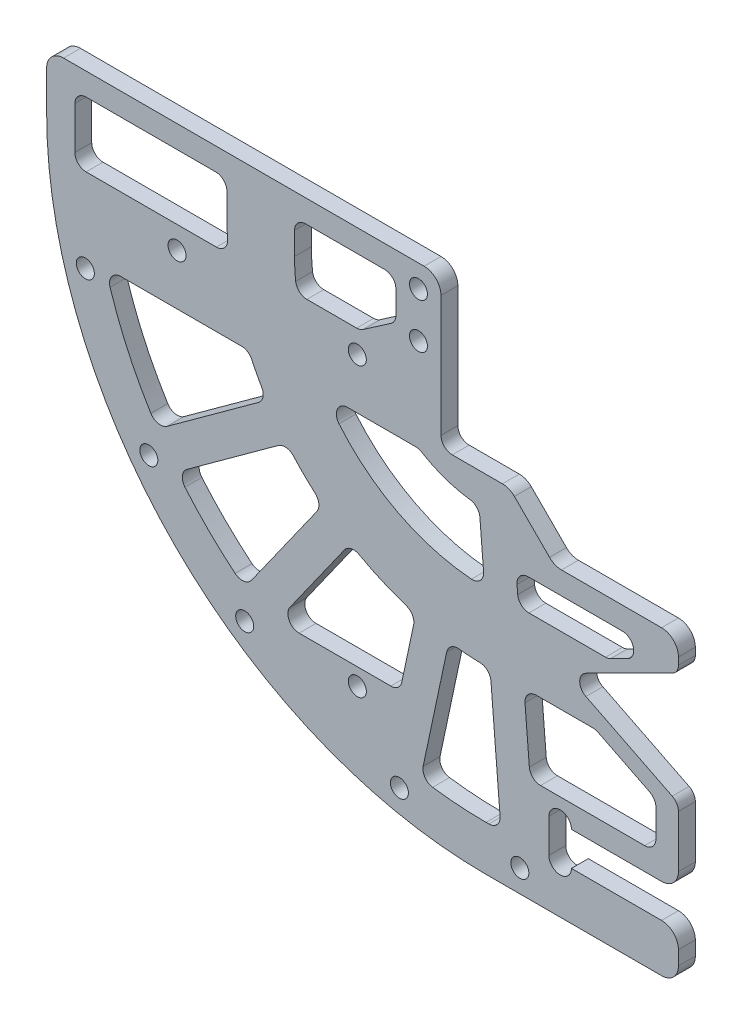
SolidWorks part; units mm, degrees
material "A-玻璃纤维"
ref_plane "前视基准面" through (0, 0, 0) normal (0, 0, 1) x (1, 0, 0)
ref_plane "上视基准面" through (0, 0, 0) normal (0, 1, 0) x (1, 0, 0)
ref_plane "右视基准面" through (0, 0, 0) normal (1, 0, 0) x (0, 0, -1)
sketch "草图1" plane through (0, 0, 0) normal (0, 0, 1) x (1, 0, 0)
  line L0 (-139.1546, 76.5) -> (-139.1546, -33.6254) construction
  line L1 (-91.6495, 50) -> (0, 50) construction
  line L2 (-90.2793, 53) -> (-5.3283, 53) construction
  line L4 (-99.1546, 26.5) -> (0, 26.5) construction
  line L6 (-99.1546, 26.5) -> (-88, 26.5) construction
  line L7 (0, 26.5) -> (0, 0) construction
  line L8 (-88, 26.5) -> (-88, -20.8435) construction
  arc A0 (-139.1546, 66.5) -> (-99.1546, 26.5) centre (-99.1546, 66.5) ccw
  dimension "D1" = 3
  dimension "D4" = 80
  dimension "D3" = 23.5
  dimension "D7" = 10
  dimension "D8" = 88
  dimension "D9" = 11.1546
sketch "草图2" plane through (0, 0, 0) normal (0, 0, 1) x (1, 0, 0)
  line L0 (0, 0) -> (-88, 0) construction
  line L1 (-88, 26.5) -> (-88, -20.8435) construction
  line L2 (0, 3) -> (-88, 3) construction
  line L3 (-99.1546, 26.5) -> (0, 26.5) construction
  line L4 (-139.1546, 76.5) -> (-139.1546, -33.6254) construction
  line L5 (-99.1546, 26.5) -> (-88, 26.5) construction
  line L6 (-139.1546, 76.5) -> (-139.1546, 66.5) construction
  line L7 (-88, 3) -> (-88, 26.5) construction
  line L8 (-161.1546, 76.5) -> (-161.1546, 66.5) construction
  line L9 (-99.1546, 4.5) -> (-88, 4.5) construction
  line L10 (-117.1546, 76.5) -> (-117.1546, 66.5) construction
  line L11 (-99.1546, 48.5) -> (-88, 48.5) construction
  line L12 (-63.5, 3) -> (-63.5, 50) construction
  line L13 (-162.1546, 76.5) -> (-162.1546, 66.5) construction
  line L14 (-99.1546, 3.5) -> (-88, 3.5) construction
  line L15 (-164.6546, 76.5) -> (-164.6546, 66.5) construction
  line L16 (-99.1546, 1) -> (-88, 1) construction
  line L17 (-169.1546, 76.5) -> (-169.1546, 66.5) construction
  line L18 (-99.1546, -3.5) -> (-88, -3.5) construction
  line L19 (-177.1546, 76.5) -> (-177.1546, 66.5)
  line L20 (-99.1546, -11.5) -> (-88, -11.5)
  line L21 (-177.1546, 76.5) -> (-162.1546, 76.5) construction
  line L22 (-88, 3.5) -> (-88, -11.5) construction
  line L23 (-99.1546, 66.5) -> (-99.1546, 1) construction
  line L24 (-99.1546, 66.5) -> (-106.9101, 1.4608) construction
  line L25 (-164.6546, 75.2931) -> (-164.6546, 78.7931) construction
  line L26 (-91.6495, 50) -> (0, 50) construction
  line L27 (0, -3) -> (-88, -3) construction
  line L33 (-65, 3) -> (-88, 3)
  line L34 (-88, 3) -> (-88, -3)
  line L35 (-88, -3) -> (-65, -3)
  line L36 (-65, -3) -> (-65, -11.5)
  line L37 (-65, -11.5) -> (-88, -11.5)
  line L38 (-177.1546, 76.5) -> (-107.1546, 76.5)
  line L39 (-107.1546, 76.5) -> (-107.1546, 50)
  line L40 (-107.1546, 50) -> (-65, 50)
  line L41 (-65, 50) -> (-65, 35.9434)
  line L42 (-65, 35.9434) -> (-62.5, 34.5)
  line L43 (-62.5, 34.5) -> (-62.5, 18.5)
  line L44 (-62.5, 18.5) -> (-65, 17.0566)
  line L45 (-65, 17.0566) -> (-65, 3)
  line L46 (-62.5, 26.5) -> (-47.2977, 26.5) construction
  arc A0 (-139.1546, 66.5) -> (-99.1546, 26.5) centre (-99.1546, 66.5) ccw construction
  arc A1 (-139.1546, 66.5) -> (-99.1546, 26.5) centre (-99.1546, 66.5) ccw construction
  arc A2 (-161.1546, 66.5) -> (-99.1546, 4.5) centre (-99.1546, 66.5) ccw construction
  arc A3 (-117.1546, 66.5) -> (-99.1546, 48.5) centre (-99.1546, 66.5) ccw construction
  arc A4 (-162.1546, 66.5) -> (-99.1546, 3.5) centre (-99.1546, 66.5) ccw construction
  arc A5 (-164.6546, 66.5) -> (-99.1546, 1) centre (-99.1546, 66.5) ccw construction
  arc A6 (-169.1546, 66.5) -> (-99.1546, -3.5) centre (-99.1546, 66.5) ccw construction
  arc A7 (-177.1546, 66.5) -> (-99.1546, -11.5) centre (-99.1546, 66.5) ccw
  circle A8 centre (-91.7546, 1) radius 3.5 construction
  circle A9 centre (-99.1546, 1) radius 3.5 construction
  circle A10 centre (-106.9101, 1.4608) radius 3.5 construction
  circle A11 centre (-114.5564, 2.8366) radius 3.5 construction
  circle A12 centre (-121.9861, 5.108) radius 3.5 construction
  circle A13 centre (-129.0945, 8.2432) radius 3.5 construction
  circle A14 centre (-135.7817, 12.198) radius 3.5 construction
  circle A15 centre (-141.9536, 16.9168) radius 3.5 construction
  circle A16 centre (-147.5234, 22.3332) radius 3.5 construction
  circle A17 centre (-152.4127, 28.3709) radius 3.5 construction
  circle A18 centre (-156.5527, 34.9451) radius 3.5 construction
  circle A19 centre (-159.8851, 41.9633) radius 3.5 construction
  circle A20 centre (-162.3632, 49.3266) radius 3.5 construction
  circle A21 centre (-163.9519, 56.9316) radius 3.5 construction
  circle A22 centre (-164.6291, 64.6711) radius 3.5 construction
  circle A23 centre (-164.6546, 72.3711) radius 3.5 construction
  arc A24 (-139.1546, 66.5) -> (-99.1546, 26.5) centre (-99.1546, 66.5) ccw construction
  dimension "D8" = 7
  dimension "D9" = 7
  dimension "D10" = 7.4
  dimension "D13" = 7
  dimension "D16" = 24.5
  dimension "D1" = 3
  dimension "D2" = 22
  dimension "D4" = 1
  dimension "D12" = 6.8
  dimension "D14" = 7.7691
  dimension "D15" = 7.7
  dimension "D17" = 3
  dimension "D18" = 120
  dimension "D19" = 120
  dimension "D20" = 23
  dimension "D21" = 1
  dimension "D22" = 16
  dimension "D23" = 10
  dimension "D3" = 22
  dimension "D5" = 3.5
  dimension "D6" = 7
  dimension "D7" = 8
  dimension "D11" = 14
extrude "凸台-拉伸1" add sketch "草图2" along normal blind 3 contours L39 L40 L41 L42 L43 L44 L45 L33 L34 L35 L36 L37 L20 A7 L19 L38
sketch "草图3" plane through (0, 0, 3) normal (0, 0, 1) x (1, 0, 0)
  line L0 (-88, 3) -> (-183.1097, 3) construction
  line L1 (-137, 6) -> (-122, 6) construction
  line L2 (-117, 9) -> (-157, 9) construction
  line L3 (-117, 9) -> (-117, 3) construction
  line L4 (-117, 3) -> (-157, 3) construction
  line L5 (-157, 9) -> (-157, 3) construction
  line L6 (-117, 9) -> (-157, 3) construction
  line L7 (-117, 3) -> (-157, 9) construction
  line L8 (-137, 6) -> (-142, 6) construction
  circle A0 centre (-142, 6) radius 1.6
  circle A1 centre (-122, 6) radius 1.6
  point P3 (-137, 6)
  dimension "D5" = 5
  dimension "D6" = 3.2
  dimension "D7" = 3.2
  dimension "D1" = 6
  dimension "D2" = 40
  dimension "D3" = 157
  dimension "D4" = 15
extrude "切除-拉伸1" cut sketch "草图3" against normal blind 10
sketch "草图4" plane through (0, 0, 3) normal (0, 0, 1) x (1, 0, 0)
  line L0 (-65, -11.5) -> (-99.1546, -11.5) construction
  line L1 (-65, -11.5) -> (-99.1546, -11.5) construction
  line L2 (-65, -7.5) -> (-99.1546, -7.5) construction
  line L3 (-185.4367, 66.5) -> (-99.1546, 66.5) construction
  line L4 (-99.1546, 66.5) -> (-170.288, 46.1028) construction
  line L5 (-159.0218, 23.0039) -> (-99.1546, 66.5) construction
  line L6 (-99.1546, 66.5) -> (-114.5401, -5.8829) construction
  line L7 (-99.1546, 66.5) -> (-99.1546, -11.5) construction
  arc A0 (-177.1546, 66.5) -> (-99.1546, -11.5) centre (-99.1546, 66.5) ccw construction
  arc A1 (-177.1546, 66.5) -> (-99.1546, -11.5) centre (-99.1546, 66.5) ccw construction
  arc A2 (-173.1546, 66.5) -> (-99.1546, -7.5) centre (-99.1546, 66.5) ccw construction
  circle A3 centre (-170.288, 46.1028) radius 1.6
  circle A4 centre (-159.0218, 23.0039) radius 1.6
  circle A5 centre (-114.5401, -5.8829) radius 1.6
  circle A6 centre (-93.1546, -7.5) radius 1.6
  dimension "D2" = 3.2
  dimension "D3" = 3.2
  dimension "D4" = 3.2
  dimension "D5" = 3.2
  dimension "D6" = 6
  dimension "D7" = 12
  dimension "D8" = 20
  dimension "D9" = 16
  dimension "D1" = 4
extrude "切除-拉伸2" cut sketch "草图4" against normal blind 10
sketch "草图5" plane through (0, 0, 3) normal (0, 0, 1) x (1, 0, 0)
  line L0 (-65, 3) -> (-88, 3) construction
  line L1 (-88, -3) -> (-65, -3) construction
  line L2 (-88, 3) -> (-88, -3) construction
  circle A0 centre (-86, 3) radius 2
  circle A1 centre (-86, -3) radius 2
  dimension "D1" = 4
  dimension "D2" = 4
extrude "切除-拉伸3" cut sketch "草图5" against normal blind 10
sketch "草图6" plane through (0, 0, 3) normal (0, 0, 1) x (1, 0, 0)
  line L0 (-111.1546, 64.5) -> (-111.1546, 72.5) construction
  line L1 (-177.1546, 76.5) -> (-107.1546, 76.5) construction
  line L3 (-99.1546, 53) -> (-99.1546, 69.0606) construction
  circle A0 centre (-111.1546, 72.5) radius 1.6
  circle A1 centre (-111.1546, 64.5) radius 1.6
  dimension "D1" = 3.2
  dimension "D2" = 3.2
  dimension "D4" = 4
  dimension "D5" = 12
  dimension "D3" = 8
extrude "切除-拉伸4" cut sketch "草图6" against normal blind 3
sketch "草图7" plane through (0, 0, 3) normal (0, 0, 1) x (1, 0, 0)
  line L0 (-107.1546, 50) -> (-161.0256, 50) construction
  line L1 (-154.0101, 57) -> (-122.0101, 57) construction
  line L2 (-138.0101, 57) -> (-138.0101, 61.0464) construction
  line L4 (-162.0101, 61) -> (-114.0101, 61) construction
  line L5 (-162.0101, 61) -> (-162.0101, 53) construction
  line L6 (-162.0101, 53) -> (-114.0101, 53) construction
  line L7 (-114.0101, 61) -> (-114.0101, 53) construction
  line L8 (-162.0101, 61) -> (-114.0101, 53) construction
  line L9 (-162.0101, 53) -> (-114.0101, 61) construction
  arc A0 (-139.1546, 66.5) -> (-99.1546, 26.5) centre (-99.1546, 66.5) ccw construction
  arc A1 (-139.1546, 66.5) -> (-99.1546, 26.5) centre (-99.1546, 66.5) ccw construction
  circle A4 centre (-111.1546, 64.5) radius 1.6 construction
  circle A5 centre (-154.0101, 57) radius 1.6
  circle A6 centre (-122.0101, 57) radius 1.6
  dimension "D1" = 7
  dimension "D6" = 3.2
  dimension "D7" = 3.2
  dimension "D2" = 32
  dimension "D3" = 8
  dimension "D4" = 48
  dimension "D5" = 3.5
extrude "切除-拉伸5" cut sketch "草图7" against normal blind 3
fillet "圆角1" radius 2 1 edges at (-107.1546, 50, 1.5)
sketch "草图8" plane through (0, 0, 3) normal (0, 0, 1) x (1, 0, 0)
  line L0 (-95, 50) -> (-87, 42)
  line L1 (-105.1546, 50) -> (-65, 50) construction
  line L2 (-87, 42) -> (-65, 42)
  line L3 (-65, 50) -> (-65, 35.9434) construction
  line L4 (-65, 42) -> (-65, 50)
  line L5 (-65, 50) -> (-95, 50)
  dimension "D1" = 8
  dimension "D2" = 135
  dimension "D3" = 22
extrude "切除-拉伸6" cut sketch "草图8" against normal blind 11.6
fillet "圆角2" radius 3 8 edges at (-65, -11.5, 1.5) (-65, -3, 1.5) (-65, 3, 1.5) (-177.1546, 76.5, 1.5) (-107.1546, 76.5, 1.5) (-95, 50, 1.5) (-87, 42, 1.5) (-65, 42, 1.5)
sketch "草图9" plane through (0, 0, 3) normal (0, 0, 1) x (1, 0, 0)
  line L0 (-99.1546, 26.5) -> (0, 26.5) construction
  line L1 (-139.1546, 76.5) -> (-139.1546, -33.6254) construction
  line L2 (-99.1546, 26.5) -> (0, 26.5) construction
  line L3 (-139.1546, 76.5) -> (-139.1546, 66.5) construction
  line L4 (-145.1546, 72.5) -> (-145.1546, 66.5)
  line L5 (-99.1546, 20.5) -> (-98.4347, 20.5)
  line L6 (-133.1546, 72.5) -> (-133.1546, 66.5)
  line L7 (-101.7131, 60.933) -> (-101.3333, 56.2498)
  line L8 (-172.1546, 61) -> (-144.8246, 61)
  line L9 (-166.6657, 48) -> (-141.2705, 48)
  line L10 (-133.1546, 72.5) -> (-115.1546, 72.5)
  line L11 (-115.1546, 72.5) -> (-115.1546, 65.3828)
  line L12 (-115.1546, 65.3828) -> (-121.4982, 61)
  line L13 (-122.0101, 57) -> (-111.1546, 64.5) construction
  line L14 (-174.1546, 76.5) -> (-110.1546, 76.5) construction
  line L15 (-145.1546, 72.5) -> (-172.1546, 72.5)
  line L16 (-172.1546, 72.5) -> (-172.1546, 61)
  line L17 (-177.1546, 73.5) -> (-177.1546, 66.5) construction
  line L18 (-145.1546, 76.5) -> (-145.1546, 66.5) construction
  line L19 (-133.1546, 76.5) -> (-133.1546, 66.5) construction
  line L20 (-132.7068, 61) -> (-121.4982, 61)
  line L21 (-99.1546, 66.5) -> (-159.0218, 23.0039) construction
  line L22 (-99.1546, 66.5) -> (-142, 6) construction
  line L23 (-101.6028, 68.2338) -> (-112.1362, 53.3601)
  line L24 (-99.1546, 66.5) -> (-114.5401, -5.8829) construction
  line L25 (-99.1546, 66.5) -> (-93.1546, -7.5) construction
  line L26 (-102.089, 67.1237) -> (-105.1135, 52.8949)
  line L27 (-102.1448, 66.2576) -> (-101.3333, 56.2498)
  line L28 (-101.7131, 60.933) -> (-112.1362, 53.3601)
  line L29 (-96.7063, 64.7662) -> (-105.1135, 52.8949)
  line L30 (-96.2201, 65.8763) -> (-98.3077, 56.0551)
  line L31 (-127.6809, 48) -> (-111.0605, 48)
  line L32 (-97.3912, 64.0729) -> (-112.1362, 53.3601)
  line L34 (-101.7131, 60.933) -> (-157.2585, 20.5768) construction
  line L35 (-99.1546, -3.5) -> (-68, -3.5)
  line L36 (-99.1546, -3.5) -> (-96.4888, -3.5)
  line L37 (-97.3912, 64.0729) -> (-157.2585, 20.5768) construction
  line L38 (-101.6028, 68.2338) -> (-144.4482, 7.7338) construction
  line L39 (-96.7063, 64.7662) -> (-139.5518, 4.2662) construction
  line L40 (-102.089, 67.1237) -> (-117.4745, -5.2592) construction
  line L41 (-96.2201, 65.8763) -> (-111.6056, -6.5067) construction
  line L42 (-102.1448, 66.2576) -> (-96.1448, -7.7424) construction
  line L43 (-136.1993, 9) -> (-114.4436, 9)
  line L45 (-138.0535, 41.9465) -> (-157.4971, 27.8199)
  line L46 (-134.5268, 37.0924) -> (-153.9704, 22.9658)
  line L47 (-128.1314, 30.774) -> (-142.0214, 11.1607)
  line L48 (-123.2349, 27.3064) -> (-136.1993, 9)
  line L49 (-111.6326, 22.2247) -> (-114.4436, 9)
  line L50 (-105.7637, 20.9773) -> (-110.7606, -2.5312)
  line L51 (-98.4347, 20.5) -> (-96.4888, -3.5)
  line L52 (-92.415, 20.5) -> (-69, 20.5)
  line L53 (-99.1546, 20.5) -> (0, 20.5) construction
  line L54 (-92.415, 20.5) -> (-91.3204, 7)
  line L55 (-93.388, 32.5) -> (-66.388, 32.5)
  line L56 (-99.1546, 32.5) -> (0, 32.5) construction
  line L57 (-100.3834, 44.5343) -> (-99.4078, 32.5009)
  line L58 (-101.7131, 60.933) -> (-96.1448, -7.7424) construction
  line L59 (-93.388, 32.5) -> (-93.8339, 38)
  line L60 (-93.8339, 38) -> (-69.5634, 38)
  line L61 (-69.5634, 38) -> (-66.388, 32.5)
  line L62 (-85.7574, 42) -> (-68, 42) construction
  line L64 (-91.3204, 7) -> (-69, 7)
  line L65 (-69, 7) -> (-69, 20.5)
  line L66 (-65, 17.0566) -> (-65, 6) construction
  line L67 (-68, 3) -> (-84, 3) construction
  arc A0 (-139.1546, 66.5) -> (-99.1546, 26.5) centre (-99.1546, 66.5) ccw construction
  arc A1 (-139.1546, 66.5) -> (-99.1546, 26.5) centre (-99.1546, 66.5) ccw construction
  arc A2 (-145.1546, 66.5) -> (-144.8246, 61) centre (-99.1546, 66.5) ccw
  arc A3 (-133.1546, 66.5) -> (-132.7068, 61) centre (-99.1546, 66.5) ccw
  circle A4 centre (-122.0101, 57) radius 1.6 construction
  circle A5 centre (-111.1546, 64.5) radius 1.6 construction
  arc A6 (-111.0605, 48) -> (-100.3834, 44.5343) centre (-99.1546, 66.5) ccw
  arc A7 (-133.1546, 66.5) -> (-99.1546, 32.5) centre (-99.1546, 66.5) ccw construction
  arc A8 (-141.2705, 48) -> (-138.0535, 41.9465) centre (-99.1546, 66.5) ccw
  arc A9 (-145.1546, 66.5) -> (-99.1546, 20.5) centre (-99.1546, 66.5) ccw construction
  arc A11 (-166.6657, 48) -> (-157.4971, 27.8199) centre (-99.1546, 66.5) ccw
  arc A12 (-169.1546, 66.5) -> (-99.1546, -3.5) centre (-99.1546, 66.5) ccw
  arc A13 (-153.9704, 22.9658) -> (-142.0214, 11.1607) centre (-99.1546, 66.5) ccw
  arc A14 (-134.5268, 37.0924) -> (-128.1314, 30.774) centre (-99.1546, 66.5) ccw
  arc A15 (-110.7606, -2.5312) -> (-99.1546, -3.5) centre (-99.1546, 66.5) ccw
  circle A16 centre (-122, 6) radius 1.6 construction
  arc A17 (-123.2349, 27.3064) -> (-111.6326, 22.2247) centre (-99.1546, 66.5) ccw
  arc A18 (-105.7637, 20.9773) -> (-99.1546, 20.5) centre (-99.1546, 66.5) ccw
  arc A20 (-127.6809, 48) -> (-99.4078, 32.5009) centre (-99.1546, 66.5) ccw
  dimension "D3" = 4
  dimension "D4" = 9
  dimension "D5" = 4
  dimension "D13" = 70
  dimension "D15" = 68
  dimension "D16" = 44
  dimension "D6" = 3
  dimension "D7" = 4
  dimension "D8" = 5
  dimension "D9" = 3
  dimension "D12" = 3
  dimension "D14" = 3
  dimension "D17" = 3
  dimension "D18" = 27
  dimension "D19" = 60
  dimension "D20" = 4
  dimension "D21" = 6
  dimension "D22" = 4
  dimension "D23" = 4
  dimension "D1" = 6
  dimension "D2" = 6
  dimension "D10" = 3
  dimension "D11" = 8
extrude "切除-拉伸7" cut sketch "草图9" against normal blind 11.6 contours A2 L4 L15 L16 L8 | L6 A3 L20 L12 L11 L10 | L31 A20 L57 A6 | L9 A11 L45 A8 | A17 L48 L43 L49 | A18 L50 A15 L36 L51 L5 | A14 L46 A13 L47 | L61 L60 L59 L55 | L64 L65 L52 L54
sketch "草图11" plane through (0, 0, 3) normal (0, 0, 1) x (1, 0, 0)
  line L0 (-65, 36.5) -> (-85, 26.5)
  line L1 (-65, 39) -> (-65, 35.9434) construction
  line L2 (-99.1546, 26.5) -> (0, 26.5) construction
  line L3 (-85, 26.5) -> (-59.8005, 26.5) construction
  line L4 (-65, 36.5) -> (-59.8005, 36.5)
  line L5 (-59.8005, 36.5) -> (-59.8005, 16.5)
  line L6 (-62.5, 34.5) -> (-62.5, 18.5) construction
  line L7 (-65, 17.0566) -> (-65, 6) construction
  line L8 (-65, 16.5) -> (-59.8005, 16.5)
  line L9 (-65, 16.5) -> (-85, 26.5)
  dimension "D1" = 10
  dimension "D2" = 2.6995
  dimension "D3" = 20
sketch "草图13" plane through (0, 0, 3) normal (0, 0, 1) x (1, 0, 0)
  line L0 (-74.0498, 34.2111) -> (-77.4721, 32.5)
  line L1 (-69.5634, 38) -> (-66.388, 32.5) construction
  line L2 (-93.388, 32.5) -> (-66.388, 32.5) construction
  line L3 (-77.4721, 32.5) -> (-73, 32.5)
  line L4 (-65, 36.5) -> (-85, 26.5) construction
  line L5 (-73, 32.5) -> (-67.8691, 35.0654)
  line L6 (-67.8691, 35.0654) -> (-68.8709, 36.8006)
  line L7 (-93.8339, 38) -> (-69.5634, 38) construction
  line L8 (-74.9443, 38) -> (-69.5634, 38)
  line L9 (-69.5634, 38) -> (-68.8709, 36.8006)
  line L10 (-79.7082, 20.5) -> (-73, 20.5)
  line L11 (-92.415, 20.5) -> (-69, 20.5) construction
  line L12 (-65, 16.5) -> (-85, 26.5) construction
  line L13 (-73, 20.5) -> (-69, 18.5)
  line L14 (-69, 18.5) -> (-69, 15.1459)
  line L15 (-69, 7) -> (-69, 20.5) construction
  line L16 (-69, 15.1459) -> (-79.7082, 20.5)
  arc A0 (-74.0498, 34.2111) -> (-74.9443, 38) centre (-74.9443, 36) ccw
  dimension "D2" = 4
  dimension "D1" = 2
  dimension "D3" = 3
extrude "凸台-拉伸2" add sketch "草图13" against normal up to surface (3 mm away) up to face at (-151.1009, 41.3353, 0)
extrude "切除-拉伸8" cut sketch "草图11" against normal through all contours L4 L5 L8 L9 L0
fillet "圆角3" radius 2 37 edges at (-111.6326, 22.2247, 1.5) (-114.4436, 9, 1.5) (-136.1993, 9, 1.5) (-123.2349, 27.3064, 1.5) (-111.0605, 48, 1.5) (-100.3834, 44.5343, 1.5) (-99.4078, 32.5009, 1.5) (-127.6809, 48, 1.5) (-115.1546, 72.5, 1.5) (-115.1546, 65.3828, 1.5) (-121.4982, 61, 1.5) (-132.7068, 61, 1.5) (-133.1546, 72.5, 1.5) (-128.1314, 30.774, 1.5) (-142.0214, 11.1607, 1.5) (-153.9704, 22.9658, 1.5) (-134.5268, 37.0924, 1.5) (-144.8246, 61, 1.5) (-172.1546, 61, 1.5) (-172.1546, 72.5, 1.5) (-145.1546, 72.5, 1.5) (-92.415, 20.5, 1.5) (-69, 15.1459, 1.5) (-69, 7, 1.5) (-91.3204, 7, 1.5) (-98.4347, 20.5, 1.5) (-96.4888, -3.5, 1.5) (-110.7606, -2.5312, 1.5) (-105.7637, 20.9773, 1.5) (-141.2705, 48, 1.5) (-138.0535, 41.9465, 1.5) (-157.4971, 27.8199, 1.5) (-166.6657, 48, 1.5) (-93.388, 32.5, 1.5) (-93.8339, 38, 1.5) (-77.4721, 32.5, 1.5) (-79.7082, 20.5, 1.5)
fillet "圆角4" radius 2 3 edges at (-85, 26.5, 1.5) (-65, 36.5, 1.5) (-65, 16.5, 1.5)
